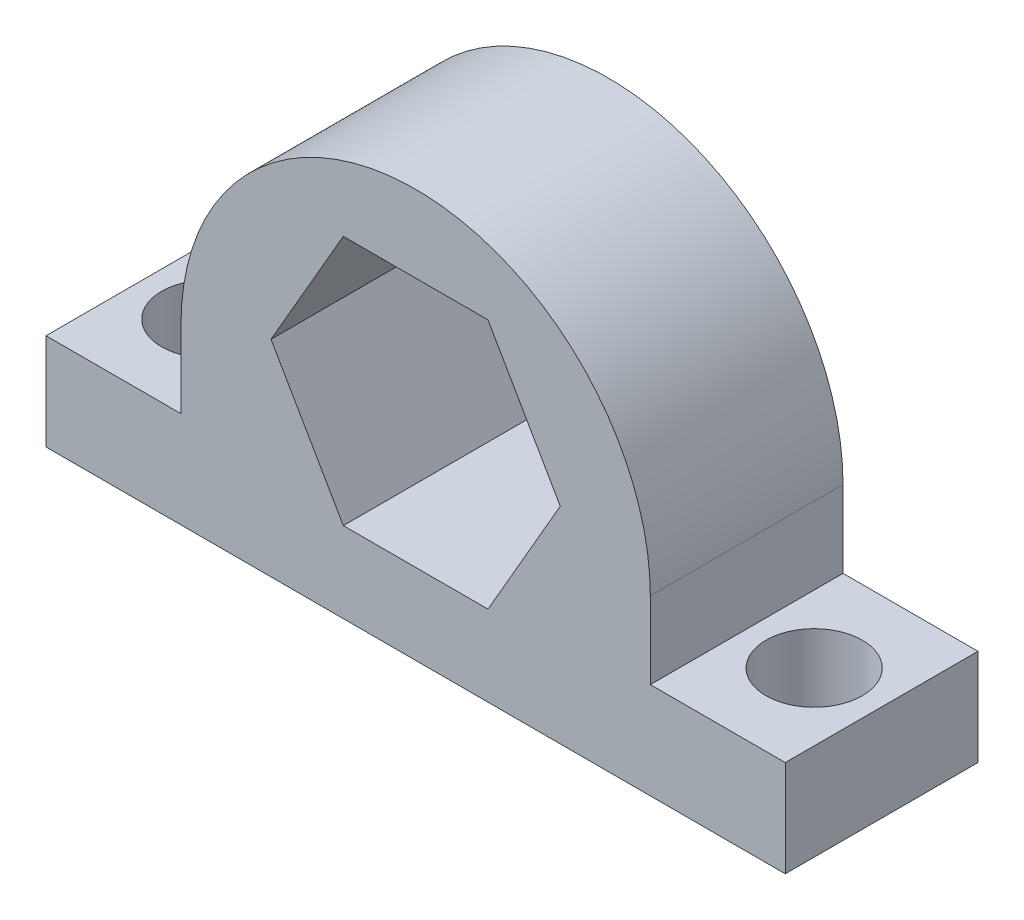
SolidWorks part; units mm, degrees
ref_plane "Front Plane" through (0, 0, 0) normal (0, 0, 1) x (1, 0, 0)
ref_plane "Top Plane" through (0, 0, 0) normal (0, 1, 0) x (1, 0, 0)
ref_plane "Right Plane" through (0, 0, 0) normal (1, 0, 0) x (0, 0, -1)
sketch "Sketch1" plane through (0, 0, 0) normal (0, 0, 1) x (1, 0, 0)
  line L0 (-16, 0) -> (16, 0)
  line L4 (-16, 5) -> (-12.177, 5)
  line L5 (-16, 0) -> (-19.18, 0)
  line L6 (-19.18, 0) -> (-19.18, 5)
  line L7 (-19.18, 5) -> (-16, 5)
  line L8 (16, 0) -> (19.18, 0)
  line L9 (16, 5) -> (19.18, 5)
  line L10 (19.18, 5) -> (19.18, 0)
  line L11 (-12.177, 8.9956) -> (-12.177, 5)
  line L12 (12.177, 8.9956) -> (12.177, 5)
  line L13 (12.177, 5) -> (16, 5)
  line L15 (7.5044, 10.68) -> (3.7522, 17.179)
  line L16 (3.7522, 17.179) -> (-3.7522, 17.179)
  line L17 (-3.7522, 17.179) -> (-7.5044, 10.68)
  line L18 (-7.5044, 10.68) -> (-3.7522, 4.181)
  line L19 (-3.7522, 4.181) -> (3.7522, 4.181)
  line L20 (3.7522, 4.181) -> (7.5044, 10.68)
  arc A0 (-12.177, 8.9956) -> (12.177, 8.9956) centre (0, 8.9956) cw
  circle A1 centre (0, 10.68) radius 6.499 construction
  circle A2 centre (0, 10.68) radius 3.9 construction
  point P4 (0, 0)
  point P10 (0, 5)
extrude "Boss-Extrude1" add sketch "Sketch1" along normal blind 10
sketch "Sketch2" plane through (0, 5, 0) normal (0, 1, 0) x (1, 0, 0)
  circle A0 centre (15.6785, -5) radius 2.5
  circle A1 centre (-15.6785, -5) radius 2.5
  dimension "D1" = 5
extrude "Cut-Extrude1" cut sketch "Sketch2" against normal blind 10
